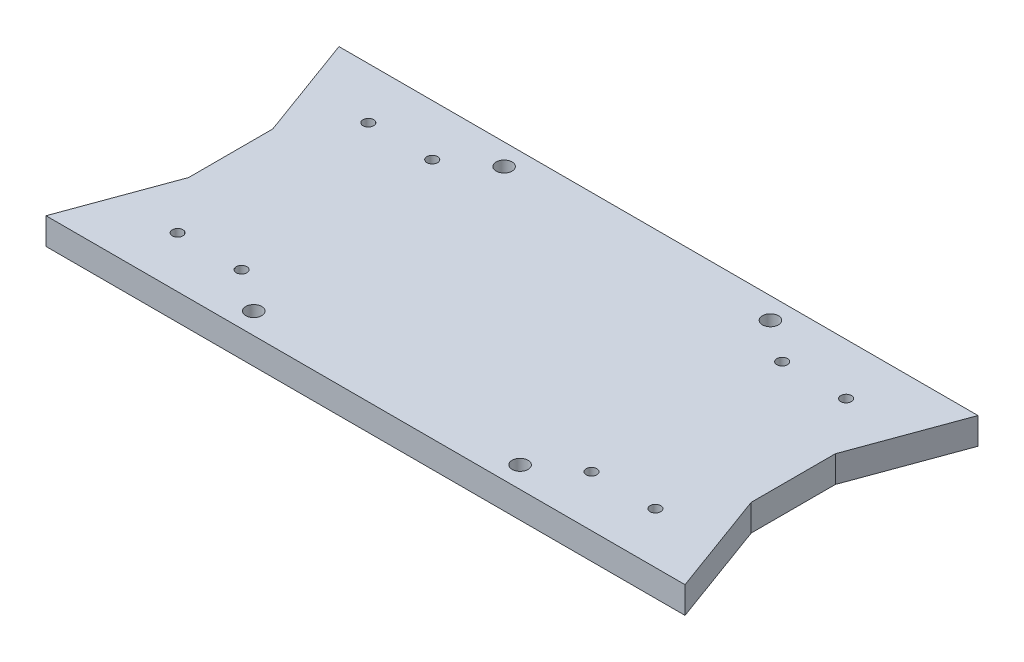
SolidWorks part; units mm, degrees
ref_plane "Front Plane" through (0, 0, 0) normal (0, 0, 1) x (1, 0, 0)
ref_plane "Top Plane" through (0, 0, 0) normal (0, 1, 0) x (1, 0, 0)
ref_plane "Right Plane" through (0, 0, 0) normal (1, 0, 0) x (0, 0, -1)
sketch "Sketch1" plane through (0, 0, 0) normal (0, 1, 0) x (1, 0, 0)
  line L0 (28.7276, 102.6327) -> (-38.3337, 102.6327) construction
  line L1 (-38.3337, 32.7827) -> (28.7276, 32.7827)
  line L2 (-38.3337, 32.7827) -> (-38.3337, 102.6327)
  line L3 (-38.3337, 102.6327) -> (28.7276, 102.6327)
  line L4 (28.7276, 32.7827) -> (28.7276, 102.6327)
  line L5 (-38.3337, 32.7827) -> (28.7276, 32.7827) construction
  line L6 (-38.3337, 102.6327) -> (-38.3337, 32.7827) construction
  circle A1 centre (3.3813, 90.4077) radius 1.27
  circle A2 centre (18.6213, 90.4077) radius 1.27
  circle A3 centre (3.3813, 44.9477) radius 1.27
  circle A4 centre (18.6213, 44.9477) radius 1.27
  dimension "D5" = 2.54
  dimension "D6" = 2.54
  dimension "D7" = 2.54
  dimension "D8" = 2.54
  dimension "D1" = 0
  dimension "D2" = 0
  dimension "D3" = 0
  dimension "D4" = 0
extrude "Boss-Extrude1" add sketch "Sketch1" along normal blind 6.35
sketch "Sketch2" plane through (0, 6.35, 0) normal (0, 1, 0) x (1, 0, 0)
  line L1 (28.7276, 57.6777) -> (7.7513, 57.6777)
  line L2 (28.7276, 57.6777) -> (28.7276, 77.7377)
  line L3 (28.7276, 77.7377) -> (7.7513, 77.7377)
  line L4 (7.7513, 57.6777) -> (7.7513, 77.7377)
extrude "Boss-Extrude2" add sketch "Sketch2" along normal blind 12.7
sketch "Sketch3" plane through (0, 6.35, 0) normal (0, 1, 0) x (1, 0, 0)
  line L1 (37.8413, 102.6327) -> (28.7276, 77.7377)
  line L2 (28.7276, 77.7377) -> (28.7276, 102.6327)
  line L3 (28.7276, 102.6327) -> (37.8413, 102.6327)
  line L4 (28.7276, 57.6777) -> (37.8413, 32.7827)
  line L5 (37.8413, 32.7827) -> (28.7276, 32.7827)
  line L6 (28.7276, 32.7827) -> (28.7276, 57.6777)
extrude "Boss-Extrude3" add sketch "Sketch3" against normal blind 6.35
mirror "Mirror2" about plane through (-38.3337, 6.35, -32.7827) normal (1, 0, 0) of "Boss-Extrude1", "Boss-Extrude2", "Boss-Extrude3"
sketch "Sketch4" plane through (0, 0, -32.7827) normal (0, 0, 1) x (1, 0, 0)
  line L1 (37.8413, 6.35) -> (-133.1569, 6.35)
  line L2 (37.8413, 6.35) -> (37.8413, 24.3471)
  line L3 (37.8413, 24.3471) -> (-133.1569, 24.3471)
  line L4 (-133.1569, 6.35) -> (-133.1569, 24.3471)
extrude "Cut-Extrude1" cut sketch "Sketch4" against normal through all
sketch "Sketch5" plane through (0, 0, 0) normal (0, -1, 0) x (1, 0, 0)
  circle A1 centre (21.0248, -94.445) radius 0.1639
sketch "Sketch6" plane through (0, 0, 0) normal (0, -1, 0) x (-1, 0, 0)
  circle A0 centre (-37.8413, 67.7077) radius 31.75
  dimension "D1" = 63.5
sketch "Sketch7" plane through (0, 6.35, 0) normal (0, 1, 0) x (1, 0, 0)
  circle A0 centre (3.3813, 90.4077) radius 1.2687
  circle A1 centre (18.6213, 90.4077) radius 1.2687
  circle A2 centre (3.3813, 44.9477) radius 1.2687
  circle A4 centre (18.6213, 44.9477) radius 1.2687
  dimension "D1" = 2.5375
  dimension "D2" = 2.5375
  dimension "D3" = 2.5375
  dimension "D4" = 2.5375
sketch "Sketch8" plane through (0, 6.35, 0) normal (0, 1, 0) x (1, 0, 0)
  circle A4 centre (-6.5587, 97.5527) radius 1.905
  circle A5 centre (-6.5587, 37.8627) radius 1.905
  circle A6 centre (-6.5587, 37.8627) radius 1.2446 construction
  circle A7 centre (-171.9188, 187.896) radius 1.905
  circle A8 centre (-70.0587, 97.5527) radius 1.905
  circle A9 centre (-70.0587, 37.8627) radius 1.905
  circle A10 centre (-70.0587, 37.8627) radius 1.2446 construction
  circle A11 centre (-70.0587, 97.5527) radius 1.2446 construction
  circle A12 centre (-6.5587, 97.5527) radius 1.2446 construction
  point P2 (0, 0)
  point P7 (-72.5565, 86.6828)
  point P12 (-7.9525, 89.7499)
  point P15 (-68.9987, 43.6777)
  dimension "D1" = 3.81
extrude "Cut-Extrude3" cut sketch "Sketch8" against normal blind 13.716
